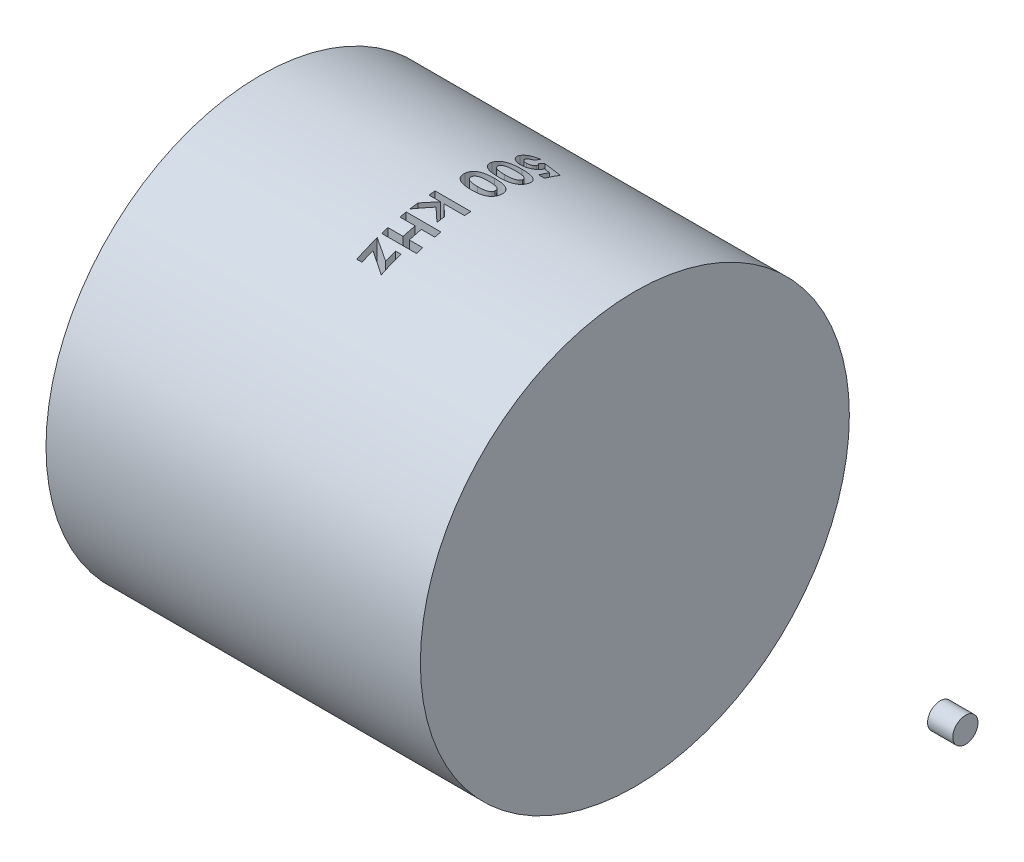
SolidWorks part; units mm, degrees
ref_plane "Front Plane" through (0, 0, 0) normal (0, 0, 1) x (1, 0, 0)
ref_plane "Top Plane" through (0, 0, 0) normal (0, 1, 0) x (1, 0, 0)
ref_plane "Right Plane" through (0, 0, 0) normal (1, 0, 0) x (0, 0, -1)
sketch "Sketch1" plane through (0, 0, 0) normal (0, 0, 1) x (1, 0, 0)
  line L0 (0, 0) -> (0, 21.59)
  line L1 (0, 21.59) -> (37.6809, 21.59)
  line L2 (37.6809, 21.59) -> (37.6809, 0)
  line L3 (0, 0) -> (37.6809, 0)
  line L4 (70.9509, 0) -> (70.9509, 1.27)
  line L5 (70.9509, 1.27) -> (68.4109, 1.27)
  line L6 (68.4109, 1.27) -> (68.4109, 0)
  line L7 (0, 0) -> (68.4109, 0) construction
  line L8 (70.9509, 0) -> (68.4109, 0)
  point P3 (69.6809, 0)
  dimension "D1" = 37.6809
  dimension "D2" = 21.59
  dimension "D3" = 32
  dimension "D4" = 2.54
  dimension "D5" = 1.27
revolve "Revolve1" add sketch "Sketch1" angle 360 about L7
sketch "Sketch2" plane through (0, 0, 0) normal (0, 1, 0) x (1, 0, 0)
  line L0 (18.8405, 21.59) -> (18.8405, -21.59) construction
  line L1 (37.6809, 21.59) -> (0, 21.59) construction
  line L2 (0, -21.59) -> (37.6809, -21.59) construction
  text T0 "<b>500 kHz</b>"
extrude "Cut-Extrude1" cut sketch "Sketch2" against normal blind 7.62 from offset 25.4
